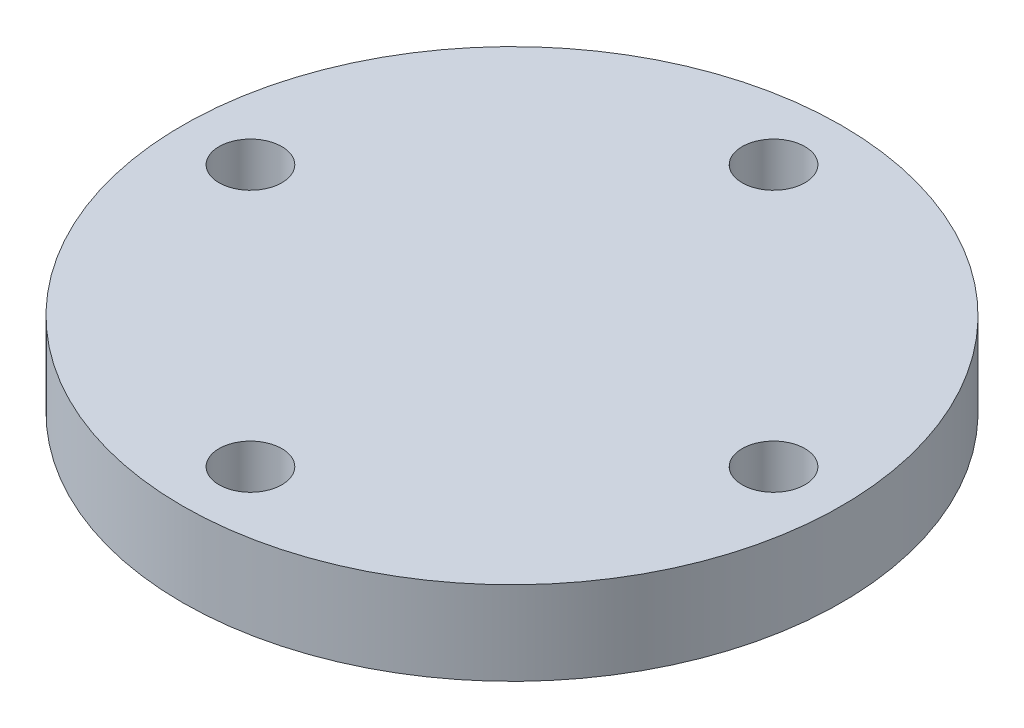
SolidWorks part; units mm, degrees
ref_plane "Front Plane" through (0, 0, 0) normal (0, 0, 1) x (1, 0, 0)
ref_plane "Top Plane" through (0, 0, 0) normal (0, 1, 0) x (1, 0, 0)
ref_plane "Right Plane" through (0, 0, 0) normal (1, 0, 0) x (0, 0, -1)
sketch "Sketch1" plane through (0, 0, 0) normal (0, 1, 0) x (1, 0, 0)
  circle A0 centre (0, 0) radius 31.5
  dimension "D1" = 63
extrude "Boss-Extrude1" add sketch "Sketch1" along normal blind 8
sketch "Sketch2" plane through (0, 8, 0) normal (0, 1, 0) x (1, 0, 0)
  circle A0 centre (0, 0) radius 25 construction
  circle A1 centre (0, 25) radius 3
  circle A2 centre (-25, 0) radius 3
  circle A3 centre (0, -25) radius 3
  circle A4 centre (25, 0) radius 3
  dimension "D1" = 50
  dimension "D2" = 6
extrude "Cut-Extrude1" cut sketch "Sketch2" against normal through all
